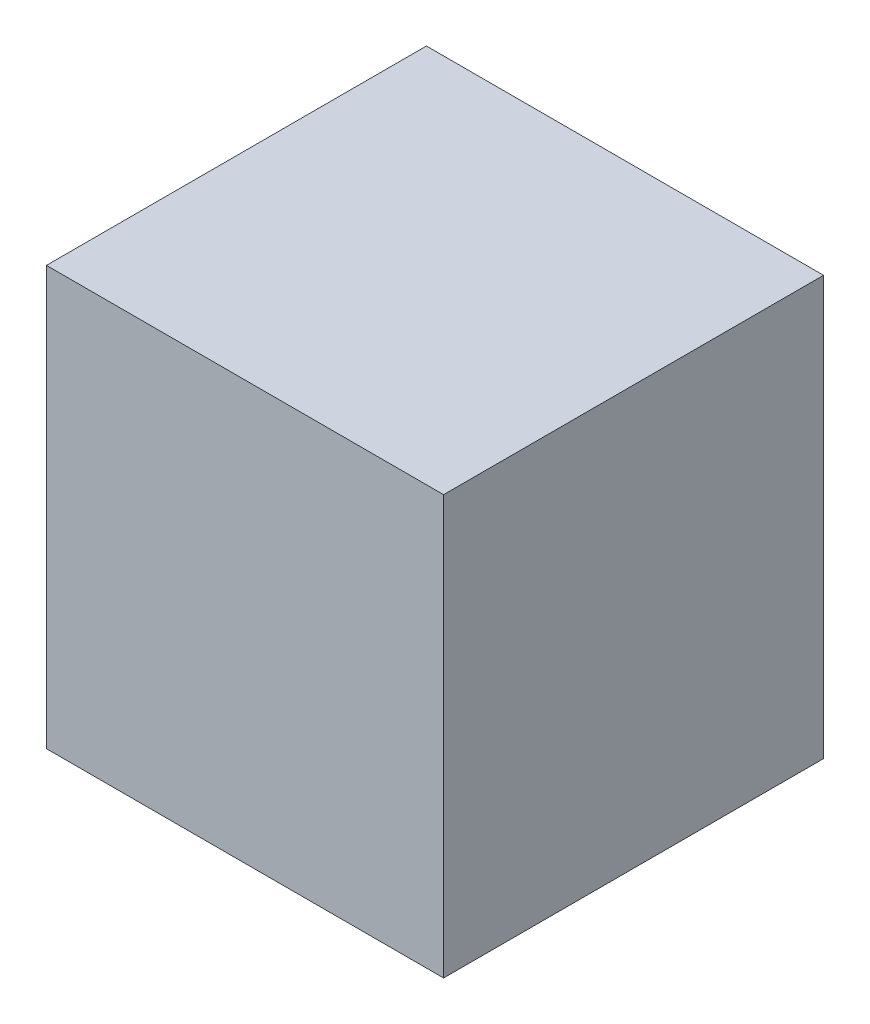
SolidWorks part; units mm, degrees
ref_plane "Front Plane" through (0, 0, 0) normal (0, 0, 1) x (1, 0, 0)
ref_plane "Top Plane" through (0, 0, 0) normal (0, 1, 0) x (1, 0, 0)
ref_plane "Right Plane" through (0, 0, 0) normal (1, 0, 0) x (0, 0, -1)
sketch "Sketch1" plane through (0, 0, 0) normal (0, 1, 0) x (1, 0, 0)
  line L1 (-234.95, -224.79) -> (234.95, -224.79)
  line L2 (-234.95, -224.79) -> (-234.95, 224.79)
  line L3 (-234.95, 224.79) -> (234.95, 224.79)
  line L4 (234.95, -224.79) -> (234.95, 224.79)
  line L5 (-234.95, -224.79) -> (234.95, 224.79) construction
  line L6 (-234.95, 224.79) -> (234.95, -224.79) construction
  point P0 (0, 0)
  dimension "D1" = 469.9
  dimension "D2" = 449.58
extrude "Boss-Extrude1" add sketch "Sketch1" along normal blind 495.3
